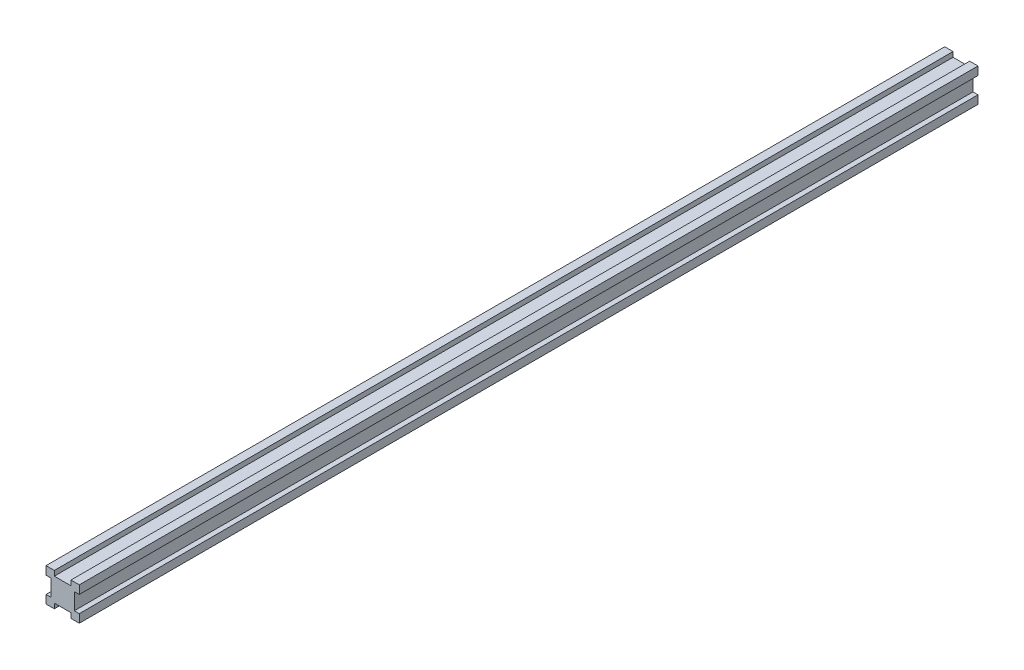
SolidWorks part; units mm, degrees
ref_plane "前视基准面" through (0, 0, 0) normal (0, 0, 1) x (1, 0, 0)
ref_plane "上视基准面" through (0, 0, 0) normal (0, 1, 0) x (1, 0, 0)
ref_plane "右视基准面" through (0, 0, 0) normal (1, 0, 0) x (0, 0, -1)
sketch "草图1" plane through (0, 0, 0) normal (0, 0, 1) x (1, 0, 0)
  line L0 (-5, 10) -> (-5, 7)
  line L1 (-10, -10) -> (10, -10)
  line L2 (-10, -10) -> (-10, -5)
  line L3 (-10, 10) -> (-5, 10)
  line L4 (10, -10) -> (10, -5)
  line L5 (-10, -10) -> (10, 10) construction
  line L6 (-10, 10) -> (10, -10) construction
  line L7 (-5, 7) -> (5, 7)
  line L8 (5, 7) -> (5, 10)
  line L9 (0, 0) -> (0, 17.8745) construction
  line L10 (7, 5) -> (7, -5)
  line L11 (10, 5) -> (7, 5)
  line L12 (7, -5) -> (10, -5)
  line L13 (5, -7) -> (-5, -7)
  line L14 (5, -10) -> (5, -7)
  line L15 (-5, -7) -> (-5, -10)
  line L16 (-7, -5) -> (-7, 5)
  line L17 (-10, -5) -> (-7, -5)
  line L18 (-7, 5) -> (-10, 5)
  line L19 (10, 5) -> (10, 10)
  line L20 (5, 10) -> (10, 10)
  line L21 (-10, 5) -> (-10, 10)
  point P0 (0, 0)
  point P27 (0, 0)
  dimension "D1" = 20
  dimension "D2" = 20
  dimension "D3" = 10
  dimension "D4" = 3
  dimension "D5" = 4
extrude "凸台-拉伸1" add sketch "草图1" along normal mid plane 540 contours L21 L18 L16 L17 L2 L1 L15 L13 L14 L4 L12 L10 L11 L19 L20 L8 L7 L0 L3
